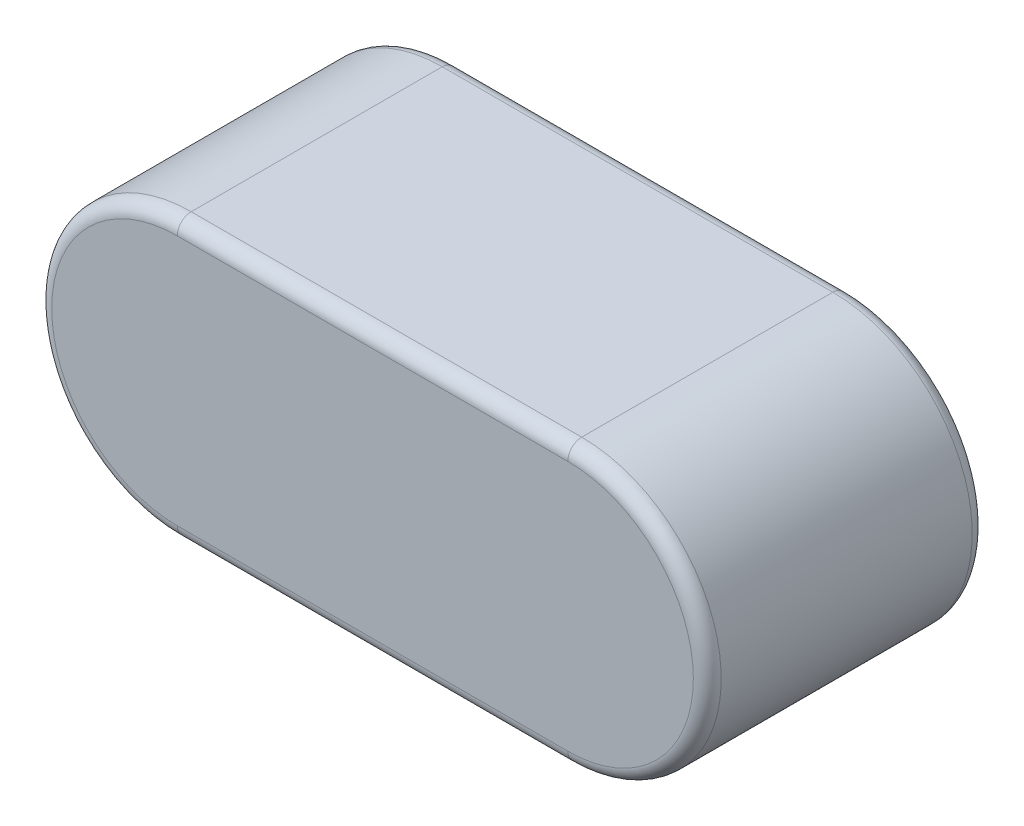
SolidWorks part; units mm, degrees
material "AISI 304"
ref_plane "Front Plane" through (0, 0, 0) normal (0, 0, 1) x (1, 0, 0)
ref_plane "Top Plane" through (0, 0, 0) normal (0, 1, 0) x (1, 0, 0)
ref_plane "Right Plane" through (0, 0, 0) normal (1, 0, 0) x (0, 0, -1)
sketch "Sketch1" plane through (0, 0, 0) normal (0, 0, 1) x (1, 0, 0)
  line L1 (0, 0) -> (7, 0)
  line L2 (0, 0) -> (0, 5)
  line L3 (0, 5) -> (7, 5)
  line L4 (7, 0) -> (7, 5)
  circle A0 centre (7, 2.5) radius 2.5
  circle A1 centre (0, 2.5) radius 2.5
  dimension "D1" = 5
  dimension "D2" = 7
extrude "Boss-Extrude1" add sketch "Sketch1" along normal blind 5 contours L2 A1 | L2 A1 | A1 L1 A0 L3 | L4 A0 | L4 A0
fillet "Fillet1" radius 0.25 8 edges at (3.5, 0, 0) (3.5, 0, 5) (9.5, 2.5, 0) (9.5, 2.5, 5) (3.5, 5, 0) (3.5, 5, 5) (-2.5, 2.5, 0) (-2.5, 2.5, 5)
